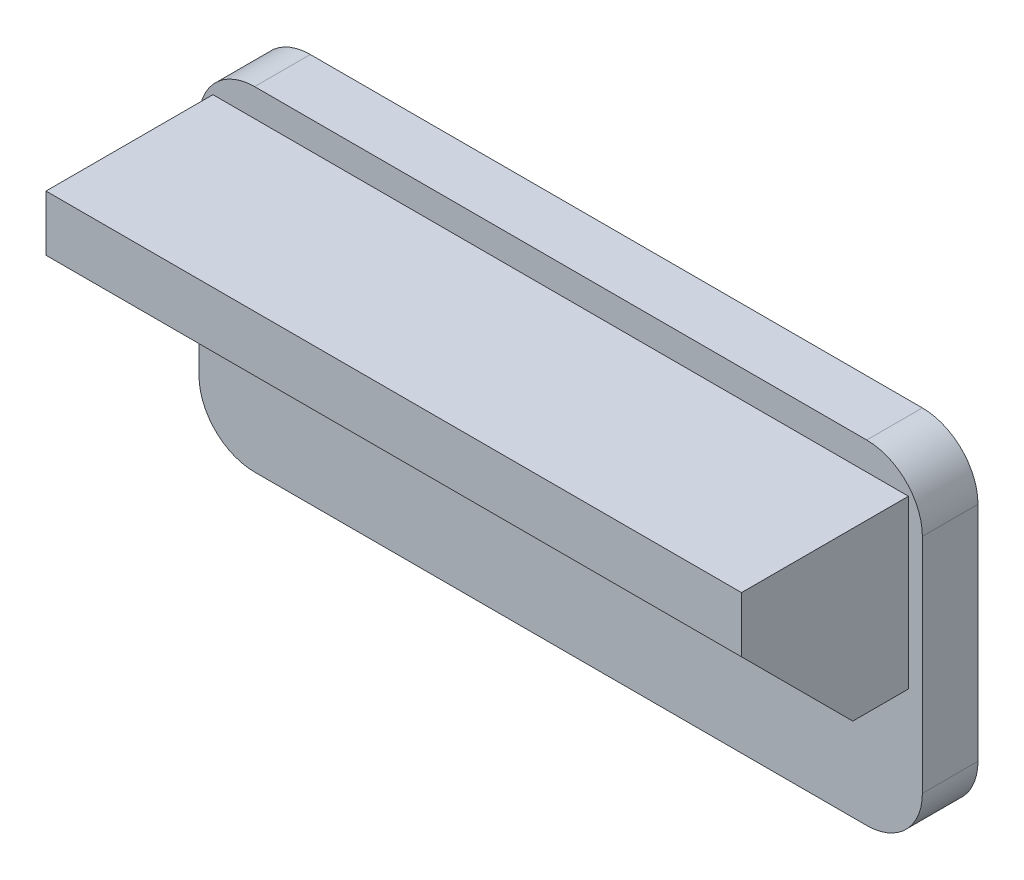
SolidWorks part; units mm, degrees
ref_plane "前视基准面" through (0, 0, 0) normal (0, 0, 1) x (1, 0, 0)
ref_plane "上视基准面" through (0, 0, 0) normal (0, 1, 0) x (1, 0, 0)
ref_plane "右视基准面" through (0, 0, 0) normal (1, 0, 0) x (0, 0, -1)
sketch "草图2" plane through (0, 0, 0) normal (0, 0, 1) x (1, 0, 0)
  line L0 (17.1197, 0) -> (-19.5806, 0) construction
  line L1 (-6.5, 3) -> (6.5, 3)
  line L2 (-6.5, 3) -> (-6.5, -3)
  line L3 (-6.5, -3) -> (6.5, -3)
  line L4 (6.5, 3) -> (6.5, -3)
  line L5 (0, 5.7376) -> (0, -7.3163) construction
  dimension "D1" = 13
  dimension "D2" = 6
extrude "凸台-拉伸1" add sketch "草图2" along normal blind 1
sketch "草图3" plane through (0, 0, 1) normal (0, 0, 1) x (1, 0, 0)
  line L0 (0, 5.5289) -> (0, -5.6142) construction
  line L1 (6.25, 2.5) -> (-6.25, 2.5)
  line L2 (-6.25, 2.5) -> (-6.25, -0.5)
  line L3 (-6.25, -0.5) -> (-5.25, -0.5)
  line L4 (-5.25, -0.5) -> (-5.25, 1.5)
  line L5 (-5.25, 1.5) -> (5.25, 1.5)
  line L6 (5.25, -0.5) -> (5.25, 1.5)
  line L7 (6.25, -0.5) -> (5.25, -0.5)
  line L8 (6.25, 2.5) -> (6.25, -0.5)
  point P10 (0, 1.5)
  point P13 (0, 2.5)
  dimension "D1" = 1
  dimension "D2" = 3
  dimension "D3" = 1
  dimension "D4" = 12.5
  dimension "D5" = 2.5
extrude "凸台-拉伸2" add sketch "草图3" along normal blind 3
chamfer "倒角1" distance 2 angle 45 2 edges at (5.75, -0.5, 4) (-5.75, -0.5, 4)
fillet "圆角1" radius 1 4 edges at (-6.5, -3, 0.5) (-6.5, 3, 0.5) (6.5, 3, 0.5) (6.5, -3, 0.5)
sketch "草图4" plane through (0, 0, 0) normal (0, 0, -1) x (-1, 0, 0)
  text T0 "USB" font "黑体" height 3.5
extrude "凸台-拉伸3" add sketch "草图4" along normal blind 0.2
